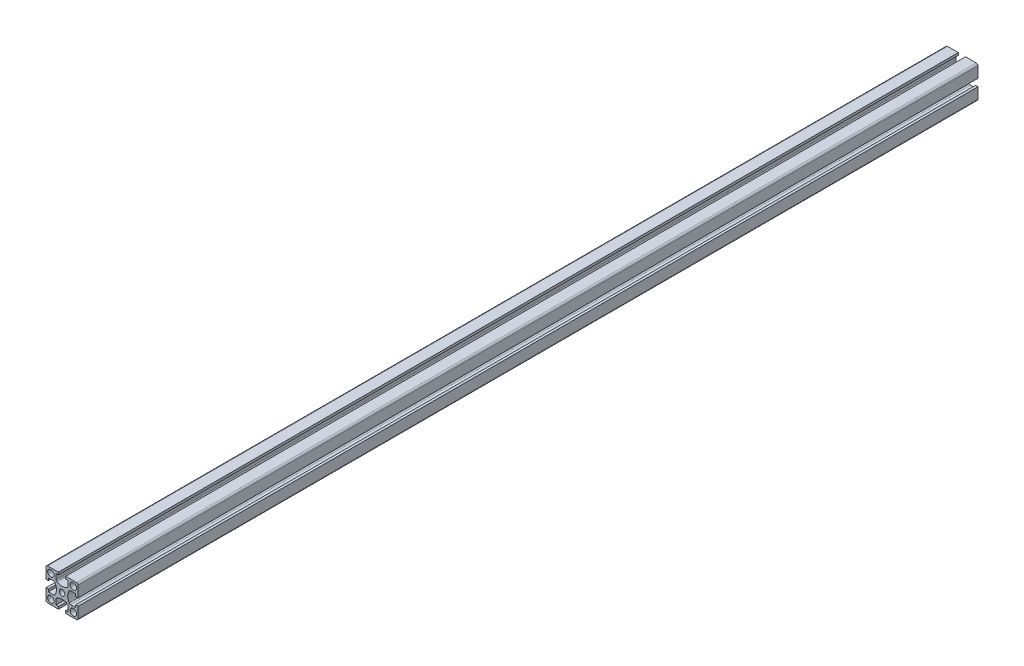
SolidWorks part; units mm, degrees
ref_plane "Front Plane" through (0, 0, 0) normal (0, 0, 1) x (1, 0, 0)
ref_plane "Top Plane" through (0, 0, 0) normal (0, 1, 0) x (1, 0, 0)
ref_plane "Right Plane" through (0, 0, 0) normal (1, 0, 0) x (0, 0, -1)
sketch "Sketch1" plane through (0, 0, 0) normal (0, 0, 1) x (1, 0, 0)
  line L64 (-10, 9) -> (-10, 2.25)
  line L65 (-10, 2.25) -> (-8.5, 2.25)
  line L66 (-8.5, 2.25) -> (-8.5, 3.75)
  line L67 (-8.5, 3.75) -> (-5.2369, 3.75)
  line L68 (-5.2369, -3.75) -> (-8.5, -3.75)
  line L69 (-8.5, -3.75) -> (-8.5, -2.25)
  line L70 (-8.5, -2.25) -> (-10, -2.25)
  line L71 (-10, -2.25) -> (-10, -9)
  line L72 (-9, -10) -> (-2.25, -10)
  line L73 (-2.25, -10) -> (-2.25, -8.5)
  line L74 (-2.25, -8.5) -> (-3.75, -8.5)
  line L75 (-3.75, -8.5) -> (-3.75, -5.2369)
  line L76 (3.75, -5.2369) -> (3.75, -8.5)
  line L77 (3.75, -8.5) -> (2.25, -8.5)
  line L78 (2.25, -8.5) -> (2.25, -10)
  line L79 (2.25, -10) -> (9, -10)
  line L80 (10, -9) -> (10, -2.25)
  line L81 (10, -2.25) -> (8.5, -2.25)
  line L82 (8.5, -2.25) -> (8.5, -3.75)
  line L83 (8.5, -3.75) -> (5.2369, -3.75)
  line L84 (5.2369, 3.75) -> (8.5, 3.75)
  line L85 (8.5, 3.75) -> (8.5, 2.25)
  line L86 (8.5, 2.25) -> (10, 2.25)
  line L87 (10, 2.25) -> (10, 9)
  line L88 (9, 10) -> (2.25, 10)
  line L89 (2.25, 10) -> (2.25, 8.5)
  line L90 (2.25, 8.5) -> (3.75, 8.5)
  line L91 (3.75, 8.5) -> (3.75, 5.2369)
  line L92 (-3.75, 5.2369) -> (-3.75, 8.5)
  line L93 (-3.75, 8.5) -> (-2.25, 8.5)
  line L94 (-2.25, 8.5) -> (-2.25, 10)
  line L95 (-2.25, 10) -> (-9, 10)
  circle A5 centre (-7, -7) radius 2
  circle A6 centre (7, -7) radius 2
  circle A7 centre (7, 7) radius 2
  circle A8 centre (0, 0) radius 1.75
  circle A9 centre (-7, 7) radius 2
  arc A32 (-9, 10) -> (-10, 9) centre (-9, 9) ccw
  arc A33 (-4.3708, 3.25) -> (-5.2369, 3.75) centre (-5.2369, 2.75) ccw
  arc A34 (-4.3708, -3.25) -> (-4.3708, 3.25) centre (-10, 0) ccw
  arc A35 (-5.2369, -3.75) -> (-4.3708, -3.25) centre (-5.2369, -2.75) ccw
  arc A36 (-10, -9) -> (-9, -10) centre (-9, -9) ccw
  arc A37 (-3.25, -4.3708) -> (-3.75, -5.2369) centre (-2.75, -5.2369) ccw
  arc A38 (3.25, -4.3708) -> (-3.25, -4.3708) centre (0, -10) ccw
  arc A39 (3.75, -5.2369) -> (3.25, -4.3708) centre (2.75, -5.2369) ccw
  arc A40 (9, -10) -> (10, -9) centre (9, -9) ccw
  arc A41 (4.3708, -3.25) -> (5.2369, -3.75) centre (5.2369, -2.75) ccw
  arc A42 (4.3708, 3.25) -> (4.3708, -3.25) centre (10, 0) ccw
  arc A43 (5.2369, 3.75) -> (4.3708, 3.25) centre (5.2369, 2.75) ccw
  arc A44 (10, 9) -> (9, 10) centre (9, 9) ccw
  arc A45 (3.25, 4.3708) -> (3.75, 5.2369) centre (2.75, 5.2369) ccw
  arc A46 (-3.25, 4.3708) -> (3.25, 4.3708) centre (0, 10) ccw
  arc A47 (-3.75, 5.2369) -> (-3.25, 4.3708) centre (-2.75, 5.2369) ccw
extrude "Boss-Extrude1" add sketch "Sketch1" along normal blind 560
